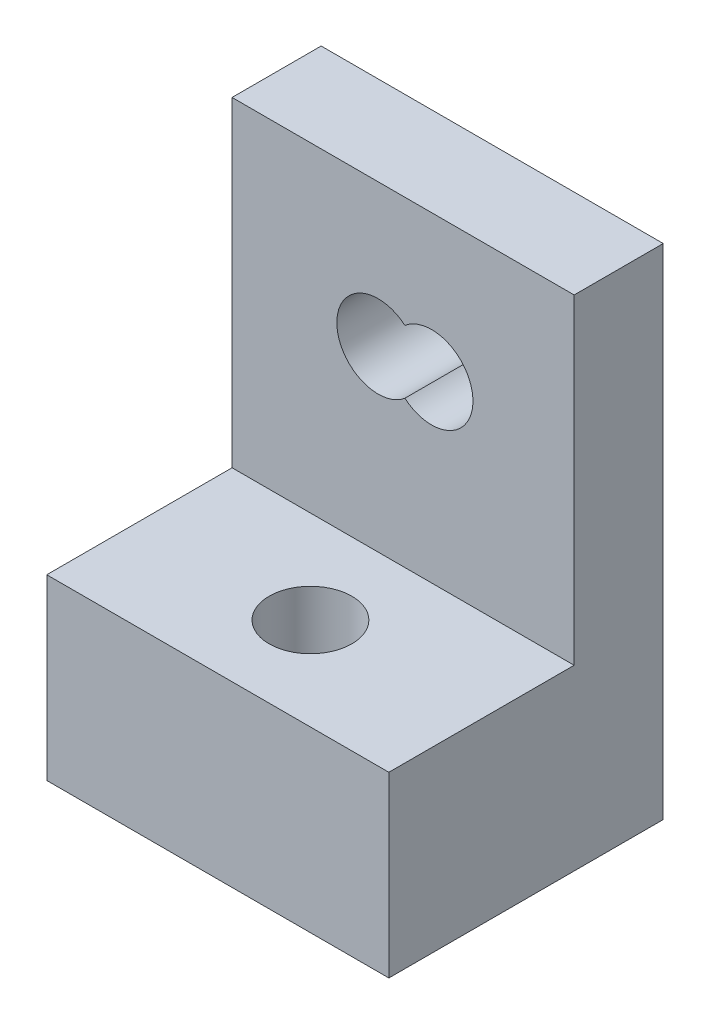
SolidWorks part; units mm, degrees
material "ABS"
ref_plane "Front Plane" through (0, 0, 0) normal (0, 0, 1) x (1, 0, 0)
ref_plane "Top Plane" through (0, 0, 0) normal (0, 1, 0) x (1, 0, 0)
ref_plane "Right Plane" through (0, 0, 0) normal (1, 0, 0) x (0, 0, -1)
sketch "Sketch1" plane through (0, 0, 0) normal (0, 1, 0) x (1, 0, 0)
  line L1 (0, 0) -> (12.192, 0)
  line L2 (0, 0) -> (0, 9.779)
  line L3 (0, 9.779) -> (12.192, 9.779)
  line L4 (12.192, 0) -> (12.192, 9.779)
  dimension "D1" = 12.192
  dimension "D2" = 9.779
extrude "Boss-Extrude1" add sketch "Sketch1" along normal blind 6.35
sketch "Sketch2" plane through (0, 6.35, 0) normal (0, 1, 0) x (1, 0, 0)
  line L1 (0, 9.779) -> (12.192, 9.779)
  line L2 (0, 9.779) -> (0, 6.604)
  line L3 (0, 6.604) -> (12.192, 6.604)
  line L4 (12.192, 9.779) -> (12.192, 6.604)
  dimension "D1" = 3.175
  dimension "D2" = 12.192
extrude "Boss-Extrude2" add sketch "Sketch2" along normal blind 11.43
sketch "Sketch3" plane through (0, 6.35, 0) normal (0, 1, 0) x (1, 0, 0)
  line L0 (0, 6.604) -> (0, 0) construction
  line L2 (0, 0) -> (12.192, 0) construction
  circle A0 centre (25.4, 3.302) radius 1.4732
  circle A1 centre (6.096, 3.302) radius 1.4732
  point P8 (0, 3.302)
  point P10 (6.096, 0)
  dimension "D1" = 2.9464
  dimension "D2" = 25.4
extrude "Cut-Extrude2" cut sketch "Sketch3" against normal blind 6.35
sketch "Sketch4" plane through (0, 0, -9.779) normal (0, 0, -1) x (-1, 0, 0)
  circle A0 centre (-5.207, 12.7) radius 1.4732
  dimension "D1" = 2.9464
extrude "Cut-Extrude3" cut sketch "Sketch4" against normal blind 6.35
sketch "Sketch5" plane through (0, 0, -9.779) normal (0, 0, -1) x (-1, 0, 0)
  circle A1 centre (-7.112, 12.7) radius 1.4732
  dimension "D1" = 2.9464
extrude "Cut-Extrude4" cut sketch "Sketch5" against normal blind 6.35
